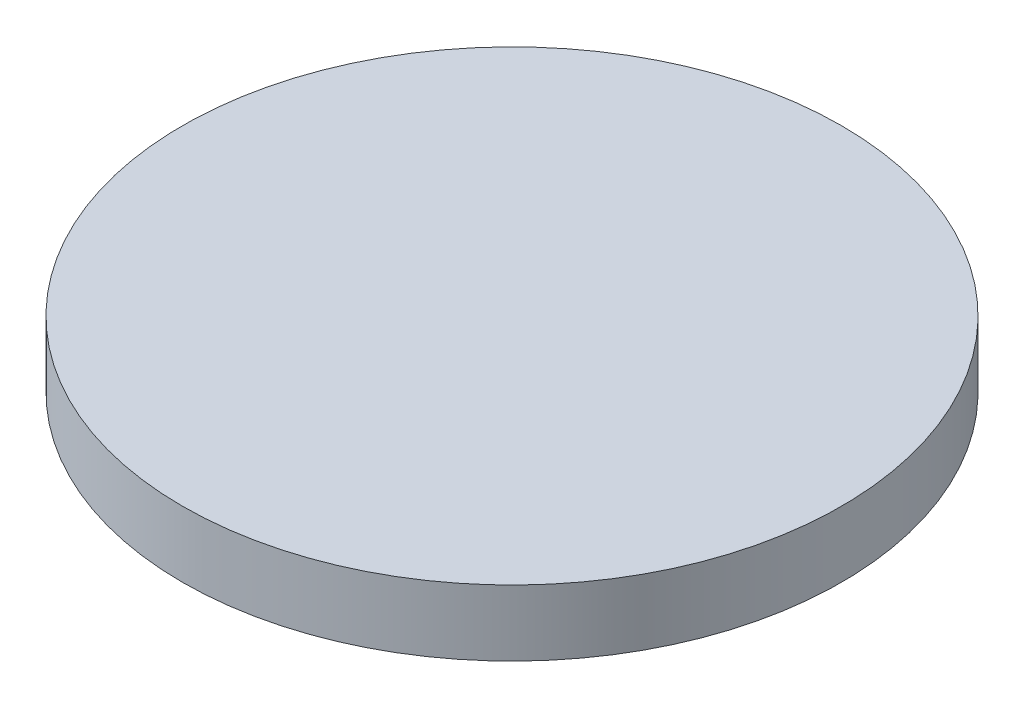
SolidWorks part; units mm, degrees
ref_plane "Alzado" through (0, 0, 0) normal (0, 0, 1) x (1, 0, 0)
ref_plane "Planta" through (0, 0, 0) normal (0, 1, 0) x (1, 0, 0)
ref_plane "Vista lateral" through (0, 0, 0) normal (1, 0, 0) x (0, 0, -1)
sketch "Croquis1" plane through (0, 0, 0) normal (0, 1, 0) x (1, 0, 0)
  circle A0 centre (0, 0) radius 50
  dimension "D1" = 100
extrude "Saliente-Extruir1" add sketch "Croquis1" along normal blind 10
